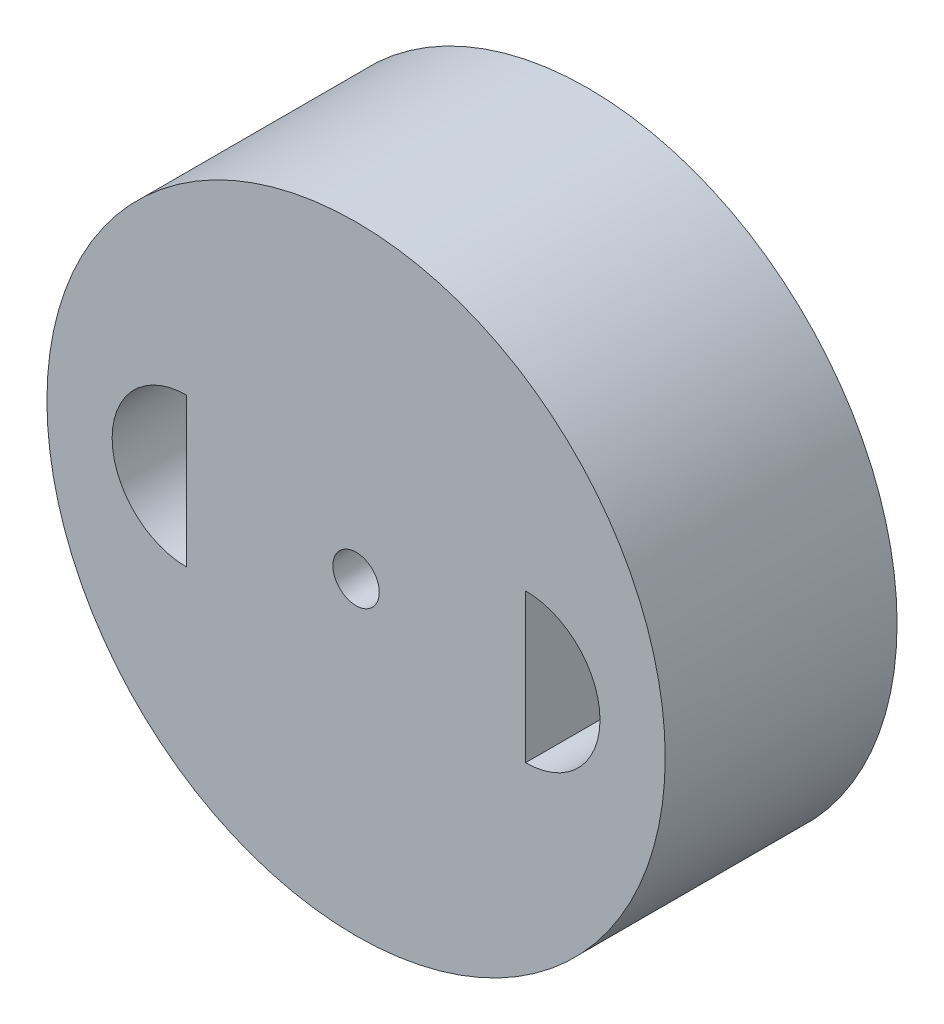
SolidWorks part; units mm, degrees
material "ABS"
ref_plane "Front Plane" through (0, 0, 0) normal (0, 0, 1) x (1, 0, 0)
ref_plane "Top Plane" through (0, 0, 0) normal (0, 1, 0) x (1, 0, 0)
ref_plane "Right Plane" through (0, 0, 0) normal (1, 0, 0) x (0, 0, -1)
sketch "Sketch1" plane through (0, 0, 0) normal (0, 0, 1) x (1, 0, 0)
  circle A0 centre (0, 0) radius 101.6
  point P23 (0, 0)
  dimension "D1" = 203.2
extrude "Boss-Extrude1" add sketch "Sketch1" along normal blind 76.2 contours A0
sketch "Sketch2" plane through (0, 0, 76.2) normal (0, 0, 1) x (1, 0, 0)
  line L8 (-55.703, 24.4622) -> (55.703, 24.4622)
  line L9 (-55.703, 24.4622) -> (-55.703, -24.4622)
  line L10 (-55.703, -24.4622) -> (55.703, -24.4622)
  line L11 (55.703, 24.4622) -> (55.703, -24.4622)
  line L12 (-55.703, 24.4622) -> (55.703, -24.4622) construction
  line L13 (-55.703, -24.4622) -> (55.703, 24.4622) construction
  arc A1 (55.703, -24.4622) -> (55.703, 24.4622) centre (55.703, 0) ccw
  arc A2 (-55.703, -24.4622) -> (-55.703, 24.4622) centre (-55.703, 0) cw
  point P0 (0, 0)
  point P14 (0, 0)
extrude "Cut-Extrude7" cut sketch "Sketch2" against normal through all both and the other way through all contours A2 L9 | L11 A1
sketch "Sketch3" plane through (0, 0, 76.2) normal (0, 0, 1) x (1, 0, 0)
  circle A0 centre (0, 0) radius 7.62
extrude "Cut-Extrude8" cut sketch "Sketch3" against normal through all
